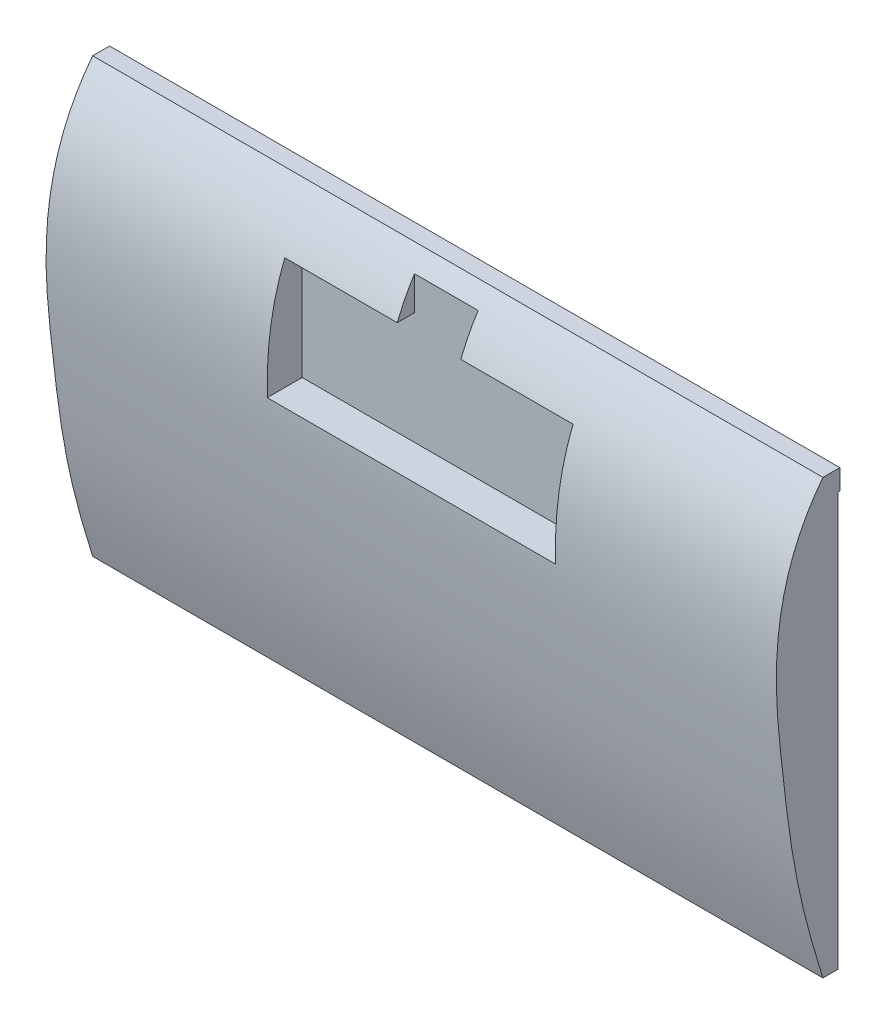
SolidWorks part; units mm, degrees
ref_plane "前基準面" through (0, 0, 0) normal (0, 0, 1) x (1, 0, 0)
ref_plane "上基準面" through (0, 0, 0) normal (0, 1, 0) x (1, 0, 0)
ref_plane "右基準面" through (0, 0, 0) normal (1, 0, 0) x (0, 0, -1)
sketch "草圖1" plane through (0, 0, 0) normal (0, 0, 1) x (1, 0, 0)
  line L1 (-269.85, 160.2) -> (269.85, 160.2)
  line L2 (-269.85, 160.2) -> (-269.85, -160.2)
  line L3 (-269.85, -160.2) -> (269.85, -160.2)
  line L4 (269.85, 160.2) -> (269.85, -160.2)
  line L5 (-269.85, 160.2) -> (269.85, -160.2) construction
  line L6 (-269.85, -160.2) -> (269.85, 160.2) construction
  point P0 (0, 0)
  dimension "D1" = 539.7
  dimension "D2" = 320.4
extrude "填料-伸長1" add sketch "草圖1" along normal blind 11
sketch "草圖3" plane through (-269.85, 0, 0) normal (-1, 0, 0) x (0, 0, 1)
  line L0 (11, 160.2) -> (11, -160.2) construction
  line L1 (11, 160.2) -> (11, -160.2)
  spline S0 degree 3 poles (11, 160.2) (53.4187, 105.582) (38.0742, -46.1984) (30.1409, -99.1605) (11, -160.2) knots 0 0 0 0 0.430835 1 1 1 1
  dimension "D1" = 31.8
extrude "填料-伸長2" add sketch "草圖3" against normal up to surface (539.7 mm away) up to face at (269.85, 0, 5.5)
ref_plane "平面1" through (0, 0, 19.5) normal (0, 0, -1) x (-1, 0, 0)
sketch "草圖4" plane through (0, 0, 19.5) normal (0, 0, -1) x (-1, 0, 0)
  line L0 (-269.85, 160.2) -> (269.85, 160.2) construction
  line L1 (-106.5, 40.2) -> (106.5, 40.2)
  line L2 (-106.5, 40.2) -> (-106.5, 123.2)
  line L3 (-106.5, 123.2) -> (106.5, 123.2)
  line L4 (106.5, 40.2) -> (106.5, 123.2)
  line L5 (-106.5, 40.2) -> (106.5, 123.2) construction
  line L6 (-106.5, 123.2) -> (106.5, 40.2) construction
  line L8 (-23.5, 123.2) -> (23.5, 123.2)
  line L9 (-23.5, 123.2) -> (-23.5, 160.2)
  line L10 (-23.5, 160.2) -> (23.5, 160.2)
  line L11 (23.5, 123.2) -> (23.5, 160.2)
  line L12 (-23.5, 123.2) -> (23.5, 160.2) construction
  line L13 (-23.5, 160.2) -> (23.5, 123.2) construction
  point P0 (0, 81.7)
  point P5 (0, 144.6796)
  point P8 (0, 141.7)
  dimension "D1" = 213
  dimension "D2" = 83
  dimension "D3" = 37
  dimension "D4" = 47
extrude "除料-伸長1" cut sketch "草圖4" against normal blind 50 contours L3 L11 L10 L9
sketch "草圖5" plane through (0, 0, 0) normal (0, 0, -1) x (-1, 0, 0)
  line L0 (-269.85, -160.2) -> (-269.85, 160.2) construction
  line L1 (269.85, 160.2) -> (-269.85, 160.2)
  line L2 (269.85, 160.2) -> (269.85, 145.2)
  line L3 (269.85, 145.2) -> (-269.85, 145.2)
  line L4 (-269.85, 160.2) -> (-269.85, 145.2)
  dimension "D1" = 15
extrude "填料-伸長3" add sketch "草圖5" along normal blind 1.5
